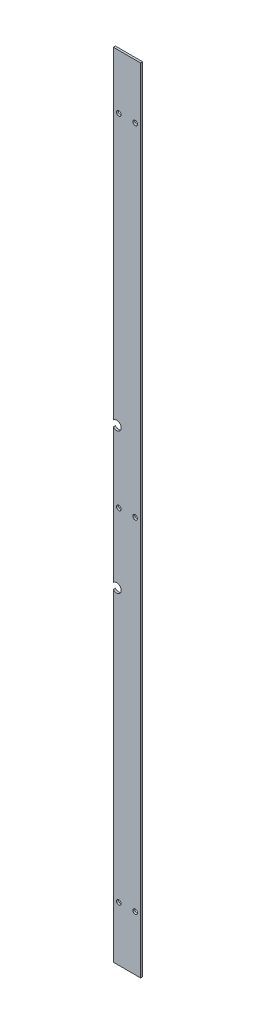
SolidWorks part; units mm, degrees
other "Top Cover Joint Strip 2"
ref_plane "Front Plane" through (0, 0, 0) normal (0, 0, 1) x (1, 0, 0)
ref_plane "Top Plane" through (0, 0, 0) normal (0, 1, 0) x (1, 0, 0)
ref_plane "Right Plane" through (0, 0, 0) normal (1, 0, 0) x (0, 0, -1)
sketch3d "Main Profile Sketch datum points"
  point P0 (0, 0, 110)
  point P1 (10, 0, 110)
  point P2 (0, 10, 110)
ref_plane "Main Profile Sketch plane" through (0, 0, 110) normal (0, 0, 1) x (1, 0, 0)
sketch "Main Profile Sketch" plane through (0, 0, 110) normal (0, 0, 1) x (1, 0, 0)
  line L0 (72.5, 49.3459) -> (72.5, -49.3459)
  line L1 (72.5, 290) -> (72.5, 53.6541)
  line L2 (72.5, 290) -> (92.5, 290)
  line L3 (92.5, 290) -> (92.5, -290)
  line L4 (72.5, -290) -> (92.5, -290)
  line L5 (72.5, -53.6541) -> (72.5, -290)
  arc A0 (72.5, -53.6541) -> (78.3, -51.5) centre (75, -51.5) ccw
  arc A1 (78.3, -51.5) -> (72.5, -49.3459) centre (75, -51.5) ccw
  arc A2 (72.5, 49.3459) -> (78.3, 51.5) centre (75, 51.5) ccw
  arc A3 (78.3, 51.5) -> (72.5, 53.6541) centre (75, 51.5) ccw
  circle A4 centre (76.5, -250) radius 1.7
  circle A5 centre (88.5, -250) radius 1.7
  circle A6 centre (76.5, 0) radius 1.7
  circle A7 centre (76.5, 250) radius 1.7
  circle A8 centre (88.5, 0) radius 1.7
  circle A9 centre (88.5, 250) radius 1.7
extrude "Main Extrusion" add sketch "Main Profile Sketch" against normal blind 1.5 separate body
